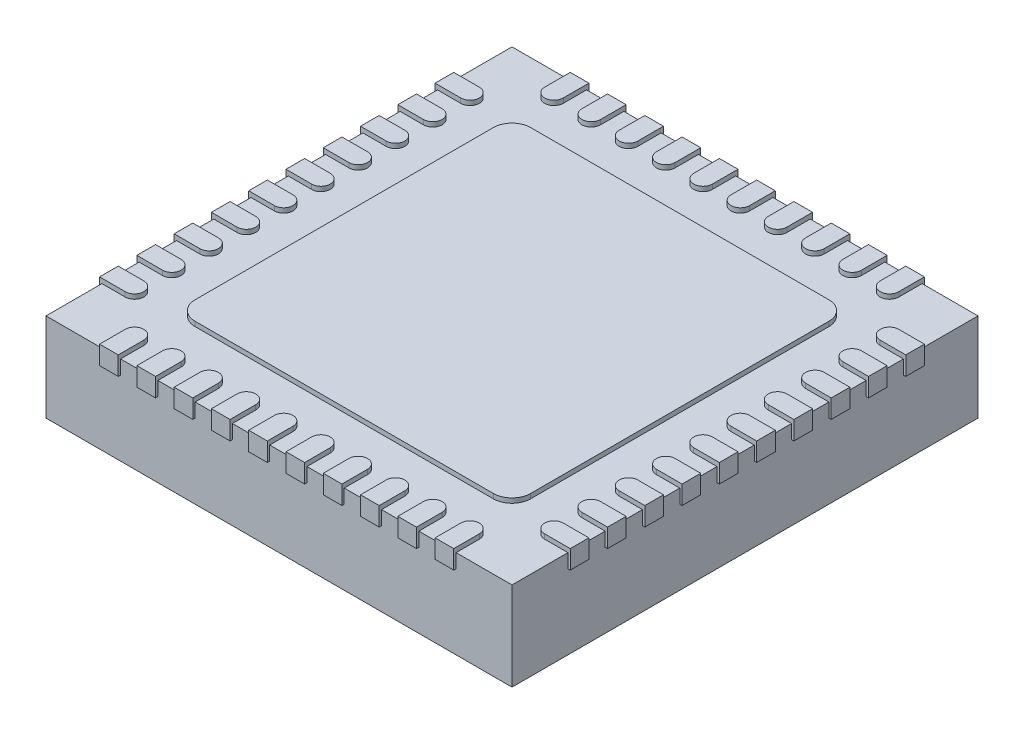
SolidWorks part; units mm, degrees
ref_plane "Front Plane" through (0, 0, 0) normal (0, 0, 1) x (1, 0, 0)
ref_plane "Top Plane" through (0, 0, 0) normal (0, 1, 0) x (1, 0, 0)
ref_plane "Right Plane" through (0, 0, 0) normal (1, 0, 0) x (0, 0, -1)
sketch "Sketch1" plane through (0, 0, 0) normal (0, 1, 0) x (1, 0, 0)
  line L0 (0, -2.75) -> (0, 2.75) construction
  line L1 (-2.525, 2.525) -> (2.525, 2.525)
  line L2 (-2.525, 2.525) -> (-2.525, -2.525)
  line L3 (-2.525, -2.525) -> (2.525, -2.525)
  line L4 (2.525, 2.525) -> (2.525, -2.525)
  line L5 (-2.75, 0) -> (2.75, 0) construction
  dimension "D1" = 5.05
  dimension "D2" = 2.525
  dimension "D3" = 2.525
sketch "Sketch2" plane through (0, 0, 0) normal (0, 1, 0) x (1, 0, 0)
  line L0 (0, -55) -> (0, 55) construction
  line L1 (-1.6, -1.8) -> (1.6, -1.8)
  line L2 (-1.8, -1.6) -> (-1.8, 1.6)
  line L3 (-1.6, 1.8) -> (1.6, 1.8)
  line L4 (1.8, -1.6) -> (1.8, 1.6)
  line L5 (-55, 0) -> (55, 0) construction
  line L6 (-1.9, -2.25) -> (-1.9, -2.525)
  line L7 (1.3, -2.25) -> (1.3, -2.525)
  line L8 (-1.9, -2.525) -> (-1.7, -2.525)
  line L9 (-1.7, -2.525) -> (-1.7, -2.25)
  line L10 (-1.9, 2.25) -> (-1.9, 2.525)
  line L11 (1.5, -2.525) -> (1.5, -2.25)
  line L12 (-1.9, 2.525) -> (-1.7, 2.525)
  line L13 (-1.7, 2.525) -> (-1.7, 2.25)
  line L14 (-1.5, -2.25) -> (-1.5, -2.525)
  line L15 (-1.3, -2.525) -> (-1.3, -2.25)
  line L16 (-1.5, -2.525) -> (-1.3, -2.525)
  line L17 (-1.3, 2.525) -> (-1.3, 2.25)
  line L18 (-1.5, 2.25) -> (-1.5, 2.525)
  line L19 (-1.5, 2.525) -> (-1.3, 2.525)
  line L20 (-1.1, -2.25) -> (-1.1, -2.525)
  line L21 (-0.9, -2.525) -> (-0.9, -2.25)
  line L22 (-1.1, -2.525) -> (-0.9, -2.525)
  line L23 (-0.9, 2.525) -> (-0.9, 2.25)
  line L24 (-1.1, 2.25) -> (-1.1, 2.525)
  line L25 (-1.1, 2.525) -> (-0.9, 2.525)
  line L26 (-0.7, -2.25) -> (-0.7, -2.525)
  line L27 (-0.5, -2.525) -> (-0.5, -2.25)
  line L28 (-0.7, -2.525) -> (-0.5, -2.525)
  line L29 (-0.5, 2.525) -> (-0.5, 2.25)
  line L30 (-0.7, 2.25) -> (-0.7, 2.525)
  line L31 (-0.7, 2.525) -> (-0.5, 2.525)
  line L32 (-0.3, -2.25) -> (-0.3, -2.525)
  line L33 (-0.1, -2.525) -> (-0.1, -2.25)
  line L34 (-0.3, -2.525) -> (-0.1, -2.525)
  line L35 (-0.1, 2.525) -> (-0.1, 2.25)
  line L36 (-0.3, 2.25) -> (-0.3, 2.525)
  line L37 (-0.3, 2.525) -> (-0.1, 2.525)
  line L38 (0.1, -2.25) -> (0.1, -2.525)
  line L39 (0.3, -2.525) -> (0.3, -2.25)
  line L40 (0.1, -2.525) -> (0.3, -2.525)
  line L41 (0.3, 2.525) -> (0.3, 2.25)
  line L42 (0.1, 2.25) -> (0.1, 2.525)
  line L43 (0.1, 2.525) -> (0.3, 2.525)
  line L44 (0.5, -2.25) -> (0.5, -2.525)
  line L45 (0.7, -2.525) -> (0.7, -2.25)
  line L46 (0.5, -2.525) -> (0.7, -2.525)
  line L47 (0.7, 2.525) -> (0.7, 2.25)
  line L48 (0.5, 2.25) -> (0.5, 2.525)
  line L49 (0.5, 2.525) -> (0.7, 2.525)
  line L50 (0.9, -2.25) -> (0.9, -2.525)
  line L51 (1.1, -2.525) -> (1.1, -2.25)
  line L52 (0.9, -2.525) -> (1.1, -2.525)
  line L53 (1.1, 2.525) -> (1.1, 2.25)
  line L54 (0.9, 2.25) -> (0.9, 2.525)
  line L55 (0.9, 2.525) -> (1.1, 2.525)
  line L56 (-2.525, -1.9) -> (-2.25, -1.9)
  line L57 (1.3, -2.525) -> (1.5, -2.525)
  line L58 (1.5, 2.525) -> (1.5, 2.25)
  line L59 (-2.25, -1.7) -> (-2.525, -1.7)
  line L60 (2.25, -1.9) -> (2.525, -1.9)
  line L61 (1.3, 2.25) -> (1.3, 2.525)
  line L62 (2.525, -1.9) -> (2.525, -1.7)
  line L63 (2.525, -1.7) -> (2.25, -1.7)
  line L64 (-2.525, -1.7) -> (-2.525, -1.9)
  line L65 (-2.25, -1.3) -> (-2.525, -1.3)
  line L66 (-2.525, -1.5) -> (-2.25, -1.5)
  line L67 (-2.525, -1.3) -> (-2.525, -1.5)
  line L68 (2.25, -1.5) -> (2.525, -1.5)
  line L69 (2.525, -1.5) -> (2.525, -1.3)
  line L70 (2.525, -1.3) -> (2.25, -1.3)
  line L71 (-2.25, -0.9) -> (-2.525, -0.9)
  line L72 (-2.525, -1.1) -> (-2.25, -1.1)
  line L73 (-2.525, -0.9) -> (-2.525, -1.1)
  line L74 (2.25, -1.1) -> (2.525, -1.1)
  line L75 (2.525, -1.1) -> (2.525, -0.9)
  line L76 (2.525, -0.9) -> (2.25, -0.9)
  line L77 (-2.25, -0.5) -> (-2.525, -0.5)
  line L78 (-2.525, -0.7) -> (-2.25, -0.7)
  line L79 (-2.525, -0.5) -> (-2.525, -0.7)
  line L80 (2.25, -0.7) -> (2.525, -0.7)
  line L81 (2.525, -0.7) -> (2.525, -0.5)
  line L82 (2.525, -0.5) -> (2.25, -0.5)
  line L83 (-2.25, -0.1) -> (-2.525, -0.1)
  line L84 (-2.525, -0.3) -> (-2.25, -0.3)
  line L85 (-2.525, -0.1) -> (-2.525, -0.3)
  line L86 (2.25, -0.3) -> (2.525, -0.3)
  line L87 (2.525, -0.3) -> (2.525, -0.1)
  line L88 (2.525, -0.1) -> (2.25, -0.1)
  line L89 (-2.25, 0.3) -> (-2.525, 0.3)
  line L90 (-2.525, 0.1) -> (-2.25, 0.1)
  line L91 (-2.525, 0.3) -> (-2.525, 0.1)
  line L92 (2.25, 0.1) -> (2.525, 0.1)
  line L93 (2.525, 0.1) -> (2.525, 0.3)
  line L94 (2.525, 0.3) -> (2.25, 0.3)
  line L95 (-2.25, 0.7) -> (-2.525, 0.7)
  line L96 (-2.525, 0.5) -> (-2.25, 0.5)
  line L97 (-2.525, 0.7) -> (-2.525, 0.5)
  line L98 (2.25, 0.5) -> (2.525, 0.5)
  line L99 (2.525, 0.5) -> (2.525, 0.7)
  line L100 (2.525, 0.7) -> (2.25, 0.7)
  line L101 (-2.25, 1.1) -> (-2.525, 1.1)
  line L102 (-2.525, 0.9) -> (-2.25, 0.9)
  line L103 (-2.525, 1.1) -> (-2.525, 0.9)
  line L104 (2.25, 0.9) -> (2.525, 0.9)
  line L105 (2.525, 0.9) -> (2.525, 1.1)
  line L106 (2.525, 1.1) -> (2.25, 1.1)
  line L107 (-2.25, -1.7) -> (-2.25, -1.3) construction
  line L108 (-2.525, 2.525) -> (-2.525, -2.525) construction
  line L109 (-2.525, 2.525) -> (2.525, 2.525) construction
  line L110 (-2.525, -2.525) -> (2.525, -2.525) construction
  line L111 (2.525, 2.525) -> (2.525, -2.525) construction
  line L112 (1.3, 2.525) -> (1.5, 2.525)
  line L113 (1.7, -2.25) -> (1.7, -2.525)
  line L114 (1.9, -2.525) -> (1.9, -2.25)
  line L115 (1.7, -2.525) -> (1.9, -2.525)
  line L116 (1.9, 2.525) -> (1.9, 2.25)
  line L117 (1.7, 2.25) -> (1.7, 2.525)
  line L118 (1.7, 2.525) -> (1.9, 2.525)
  line L119 (-2.25, 1.5) -> (-2.525, 1.5)
  line L120 (-2.525, 1.3) -> (-2.25, 1.3)
  line L121 (-2.525, 1.5) -> (-2.525, 1.3)
  line L122 (2.25, 1.3) -> (2.525, 1.3)
  line L123 (2.525, 1.3) -> (2.525, 1.5)
  line L124 (2.525, 1.5) -> (2.25, 1.5)
  line L125 (-2.25, 1.9) -> (-2.525, 1.9)
  line L126 (-2.525, 1.7) -> (-2.25, 1.7)
  line L127 (-2.525, 1.9) -> (-2.525, 1.7)
  line L128 (2.25, 1.7) -> (2.525, 1.7)
  line L129 (2.525, 1.7) -> (2.525, 1.9)
  line L130 (2.525, 1.9) -> (2.25, 1.9)
  arc A0 (1.6, 1.8) -> (1.8, 1.6) centre (1.6, 1.6) cw
  arc A1 (-1.8, 1.6) -> (-1.6, 1.8) centre (-1.6, 1.6) cw
  arc A2 (-1.6, -1.8) -> (-1.8, -1.6) centre (-1.6, -1.6) cw
  arc A3 (1.6, -1.8) -> (1.8, -1.6) centre (1.6, -1.6) ccw
  arc A4 (-1.7, -2.25) -> (-1.9, -2.25) centre (-1.8, -2.25) ccw
  arc A5 (-1.9, 2.25) -> (-1.7, 2.25) centre (-1.8, 2.25) ccw
  arc A6 (-1.3, -2.25) -> (-1.5, -2.25) centre (-1.4, -2.25) ccw
  arc A7 (-1.5, 2.25) -> (-1.3, 2.25) centre (-1.4, 2.25) ccw
  arc A8 (-0.9, -2.25) -> (-1.1, -2.25) centre (-1, -2.25) ccw
  arc A9 (-1.1, 2.25) -> (-0.9, 2.25) centre (-1, 2.25) ccw
  arc A10 (-0.5, -2.25) -> (-0.7, -2.25) centre (-0.6, -2.25) ccw
  arc A11 (-0.7, 2.25) -> (-0.5, 2.25) centre (-0.6, 2.25) ccw
  arc A12 (-0.1, -2.25) -> (-0.3, -2.25) centre (-0.2, -2.25) ccw
  arc A13 (-0.3, 2.25) -> (-0.1, 2.25) centre (-0.2, 2.25) ccw
  arc A14 (0.3, -2.25) -> (0.1, -2.25) centre (0.2, -2.25) ccw
  arc A15 (0.1, 2.25) -> (0.3, 2.25) centre (0.2, 2.25) ccw
  arc A16 (0.7, -2.25) -> (0.5, -2.25) centre (0.6, -2.25) ccw
  arc A17 (0.5, 2.25) -> (0.7, 2.25) centre (0.6, 2.25) ccw
  arc A18 (1.1, -2.25) -> (0.9, -2.25) centre (1, -2.25) ccw
  arc A19 (0.9, 2.25) -> (1.1, 2.25) centre (1, 2.25) ccw
  arc A20 (-2.25, -1.9) -> (-2.25, -1.7) centre (-2.25, -1.8) ccw
  arc A21 (2.25, -1.7) -> (2.25, -1.9) centre (2.25, -1.8) ccw
  arc A22 (-2.25, -1.5) -> (-2.25, -1.3) centre (-2.25, -1.4) ccw
  arc A23 (2.25, -1.3) -> (2.25, -1.5) centre (2.25, -1.4) ccw
  arc A24 (-2.25, -1.1) -> (-2.25, -0.9) centre (-2.25, -1) ccw
  arc A25 (2.25, -0.9) -> (2.25, -1.1) centre (2.25, -1) ccw
  arc A26 (-2.25, -0.7) -> (-2.25, -0.5) centre (-2.25, -0.6) ccw
  arc A27 (2.25, -0.5) -> (2.25, -0.7) centre (2.25, -0.6) ccw
  arc A28 (-2.25, -0.3) -> (-2.25, -0.1) centre (-2.25, -0.2) ccw
  arc A29 (2.25, -0.1) -> (2.25, -0.3) centre (2.25, -0.2) ccw
  arc A30 (-2.25, 0.1) -> (-2.25, 0.3) centre (-2.25, 0.2) ccw
  arc A31 (2.25, 0.3) -> (2.25, 0.1) centre (2.25, 0.2) ccw
  arc A32 (-2.25, 0.5) -> (-2.25, 0.7) centre (-2.25, 0.6) ccw
  arc A33 (2.25, 0.7) -> (2.25, 0.5) centre (2.25, 0.6) ccw
  arc A34 (-2.25, 0.9) -> (-2.25, 1.1) centre (-2.25, 1) ccw
  arc A35 (2.25, 1.1) -> (2.25, 0.9) centre (2.25, 1) ccw
  arc A36 (1.5, -2.25) -> (1.3, -2.25) centre (1.4, -2.25) ccw
  arc A37 (1.3, 2.25) -> (1.5, 2.25) centre (1.4, 2.25) ccw
  arc A38 (1.9, -2.25) -> (1.7, -2.25) centre (1.8, -2.25) ccw
  arc A39 (1.7, 2.25) -> (1.9, 2.25) centre (1.8, 2.25) ccw
  arc A40 (-2.25, 1.3) -> (-2.25, 1.5) centre (-2.25, 1.4) ccw
  arc A41 (2.25, 1.5) -> (2.25, 1.3) centre (2.25, 1.4) ccw
  arc A42 (-2.25, 1.7) -> (-2.25, 1.9) centre (-2.25, 1.8) ccw
  arc A43 (2.25, 1.9) -> (2.25, 1.7) centre (2.25, 1.8) ccw
  point P14 (-1.8, -1.8)
  point P17 (1.8, -1.8)
  dimension "D5" = 0.2
  dimension "D7" = 4.5
  dimension "D1" = 3.6
  dimension "D2" = 1.8
  dimension "D3" = 1.8
  dimension "D4" = 1.8
  dimension "D6" = 0.2
  dimension "D8" = 1.8
  dimension "D10" = 0.4
  dimension "D11" = 1.8
  dimension "D12" = 0.2
  dimension "D13" = 4.5
  dimension "D15" = 0.4
  dimension "D9" = 10
  dimension "D14" = 10
sketch "Sketch3" plane through (0, 0, 0) normal (0, 1, 0) x (1, 0, 0)
  line L0 (0, -2.7775) -> (0, 2.7775) construction
  line L1 (2.5, 2.5) -> (-2.5, 2.5)
  line L2 (2.5, 2.5) -> (2.5, -2.5)
  line L3 (2.5, -2.5) -> (-2.5, -2.5)
  line L4 (-2.5, 2.5) -> (-2.5, -2.5)
  line L5 (-2.7775, 0) -> (2.7775, 0) construction
  dimension "D1" = 5
  dimension "D2" = 2.5
  dimension "D3" = 2.5
  dimension "D4" = 2.5
extrude "Boss-Extrude2" add sketch "Sketch3" against normal blind 0.95
extrude "Boss-Extrude3" add sketch "Sketch2" along normal blind 0.05 and the other way blind 0.15
sketch "Sketch7" plane through (0, -0.95, 0) normal (0, -1, 0) x (1, 0, 0)
  line L0 (0, -55) -> (0, 55) construction
  line L1 (55, 0) -> (-55, 0) construction
  circle A0 centre (2.05, -2.05) radius 0.3
  dimension "D1" = 0.6
  dimension "D2" = 2.05
  dimension "D3" = 2.05
extrude "Cut-Extrude3" cut sketch "Sketch7" against normal blind 0.1
sketch "Esquisse1" plane through (0, -0.95, 0) normal (0, -1, 0) x (-1, 0, 0)
  text T0 "RTL8211" font "Century Gothic" height in points 3
extrude "Enlèv. mat.-Extru.1" cut sketch "Esquisse1" against normal blind 0.1
equation "\"D2@Sketch1\"=\"D1@Sketch1\"/2"
equation "\"D3@Sketch1\"=\"D1@Sketch1\"/2"
